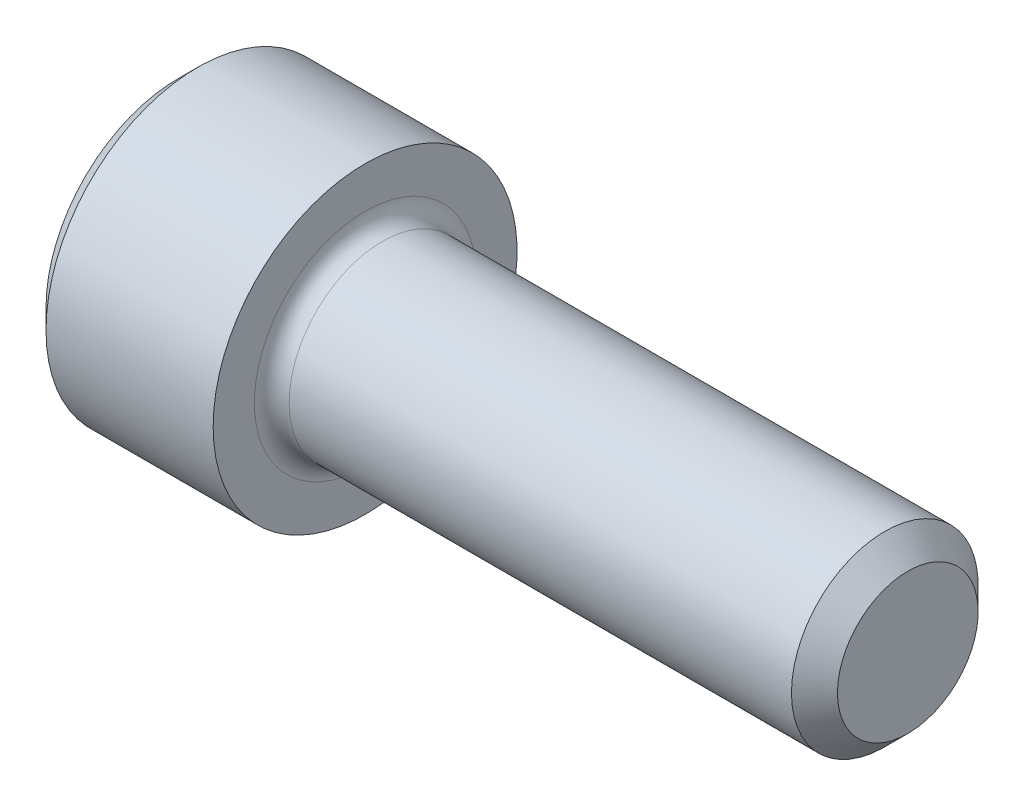
SolidWorks part; units mm, degrees
revolve "Base-Revolve" add sketch "BodySke"
sketch "BodySke" plane through (0, 0, 0) normal (0, 0, 1) x (1, 0, 0)
  line L0 (0, 0) -> (0, 1.5494)
  line L1 (0.2286, 1.778) -> (2.1844, 1.778)
  line L2 (2.1844, 1.778) -> (2.1844, 1.0922)
  line L3 (2.1844, 1.0922) -> (8.2652, 1.0922)
  line L4 (8.5344, 0.823) -> (8.5344, 0)
  line L5 (8.5344, 0) -> (0, 0)
  line L6 (-31.75, 0) -> (127, 0) construction
  line L7 (0, 1.5494) -> (0.2286, 1.778)
  line L8 (8.5344, 0.823) -> (8.2652, 1.0922)
  line L9 (0, -1.5494) -> (0.2286, -1.778) construction
  line L10 (8.5344, -0.823) -> (8.2652, -1.0922) construction
  line L11 (2.6391, 9.525) -> (2.6391, 3.175) construction
  line L12 (2.1844, 9.525) -> (2.1844, 3.175) construction
  line L13 (-29.5656, 9.525) -> (-29.5656, 3.175) construction
  dimension "Diameter" = 2.1844
  dimension "Head_ht" = 2.1844
  dimension "Length" = 6.35
  dimension "Body_ch_ang" = 45
  dimension "Head_dia" = 3.556
  dimension "Head_ch_ang" = 45
  dimension "Head_side_ht" = 1.9558
  dimension "Minor_dia" = 1.6459
  dimension "Advance" = 0.4547
  dimension "Thread_nom" = 6.35
  dimension "Thread_length" = 38.1
cosmetic thread "ThreadCosmetic" [suppressed]
fillet "Fillet1" radius 0.2032 1 edges at (2.1844, 0, 1.0922)
ref_plane "Plane1" through (0, 0, 0) normal (0, 0, 1) x (1, 0, 0)
ref_plane "Plane2" through (0, 0, 0) normal (0, 1, 0) x (1, 0, 0)
ref_plane "Plane3" through (0, 0, 0) normal (1, 0, 0) x (0, 0, -1)
sketch "Sketch2" plane through (0, 0, 0) normal (0, 0, 1) x (1, 0, 0)
  line L0 (0, 0.9906) -> (0.9652, 0.9906)
  line L1 (0.9652, 0.9906) -> (1.5371, 0)
  line L2 (-31.75, 0) -> (127, 0) construction
  line L3 (1.5371, 0) -> (0, 0)
  line L4 (0, 0) -> (0, 0.9906)
  line L5 (0, 1.5494) -> (0, -1.5494) construction
  line L6 (0, 0) -> (47.625, 0) construction
  line L7 (2.1844, -1.778) -> (2.1844, 1.778) construction
  dimension "D1" = 0.9906
  dimension "D2" = 60
revolve "Hex-PreBroach" cut sketch "Sketch2" angle 360 about L6
sketch "Sketch3" plane through (0, 0, 0) normal (-1, 0, 0) x (0, 0.5, 0.866)
  line L0 (0.5719, 0.9906) -> (-0.5719, 0.9906)
  line L1 (-0.5719, 0.9906) -> (-1.1438, 0)
  line L2 (0.5719, 0.9906) -> (1.1438, 0)
  line L3 (0.5719, -0.9906) -> (1.1438, 0)
  line L4 (0.5719, -0.9906) -> (-0.5719, -0.9906)
  line L5 (-0.5719, -0.9906) -> (-1.1438, 0)
  dimension "D1" = 0.9906
  dimension "D2" = 0.9906
  dimension "Hex_size" = 1.9812
extrude "Hex" cut sketch "Sketch3" against normal blind 0.9652
sketch "Sketch4" plane through (0, 0, 0) normal (-1, 0, 0) x (0, 0, 1)
  line L0 (0, 0) -> (1.2446, 0)
  line L1 (0, 0) -> (6.1484, 3.5498) construction
  line L2 (0, 0) -> (0.6223, 1.0779)
  line L3 (1.0085, 0.2596) -> (1.19, 0.3644)
  line L4 (0.7291, 0.7436) -> (0.9106, 0.8484)
  arc A0 (1.0085, 0.2596) -> (0.7291, 0.7436) centre (0, 0) ccw
  arc A1 (1.2446, 0) -> (1.19, 0.3644) centre (0, 0) ccw
  arc A2 (0.6223, 1.0779) -> (0.9106, 0.8484) centre (0, 0) cw
  dimension "D1" = 30
  dimension "D2" = 60
  dimension "Spline_p_dim" = 0.5588
  dimension "D3" = 0.2794
extrude "Spline" [suppressed] cut sketch "Sketch4" against normal blind 0.9652
pattern_circular "CirPattern1" [suppressed] count 6 every 60
sketch "Sketch5" plane through (0, 0, 0) normal (0, 0, 1) x (1, 0, 0)
  line L0 (-31.75, 0) -> (127, 0) construction
  line L2 (0, 1.5494) -> (0, -1.5494) construction
  circle A0 centre (0.254, 0) radius 0.0127
  dimension "Drilled_hole_dia" = 0.0254
  dimension "Drilled_hole_loc" = 0.254
extrude "Hole" [suppressed] cut sketch "Sketch5" against normal through all and the other way through all
pattern_circular "Drilled-4" [suppressed] count 2 every 60
pattern_circular "Drilled-6" [suppressed] count 3 every 60
sketch "ThdSchSke" plane through (0, 0, 0) normal (0, 0, 1) x (1, 0, 0)
  line L0 (2.6391, -0.823) -> (2.4505, -1.0922)
  line L1 (2.6391, -0.823) -> (2.8276, -1.0922)
  line L2 (2.8276, -1.0922) -> (2.8276, -1.3653)
  line L3 (-3.175, 0) -> (5.1513, 0) construction
  line L5 (2.8276, -1.3653) -> (2.4505, -1.3653)
  line L6 (2.4505, -1.3653) -> (2.4505, -1.0922)
  line L7 (0, 1.5494) -> (0, -1.5494) construction
  dimension "Thread_minor" = 1.6459
  dimension "Diameter" = 2.1844
  dimension "Start" = 2.6391
revolve "ThreadSchematic" [suppressed] cut sketch "ThdSchSke" angle 360 about L3
pattern_linear "ThdSchPat" [suppressed]
equation "\"D2@Sketch3\" = \"Hex_size@Sketch3\" / 2"
equation "\"D1@Sketch3\" = \"Hex_size@Sketch3\" / 2"
equation "\"D1@Sketch2\" = \"Hex_size@Sketch3\" / 2"
equation "\"D3@Sketch4\" = \"Spline_p_dim@Sketch4\" / 2"
equation "\"Thread_minor@ThreadCosmetic\"  =  \"Minor_dia@BodySke\""
equation "\"D2@CirPattern1\" = 360 / \"Num_teeth@CirPattern1\""
equation "\"Wall_thickness@Sketch2\" = \"Head_ht@BodySke\" - \"Key_eng@Hex\""
equation "\"Thread_length@ThreadCosmetic\" = ((sgn( (\"Length@BodySke\" - \"Advance@BodySke\" ) - \"Thread_nom@BodySke\" )-1)*( (\"Length@BodySke\" - \"Advance@BodySke\" ) - \"Thread_nom@BodySke\" ))/-2+ \"Thread_nom@BodySke\""
equation "\"Thread_minor@ThdSchSke\" = \"Minor_dia@BodySke\""
equation "\"Diameter@ThdSchSke\" = \"Diameter@BodySke\""
equation "\"Overcut@ThdSchSke\" = \"Diameter@BodySke\" * 1.25"
equation "\"Start@ThdSchSke\" = \"Head_ht@BodySke\" + \"Length@BodySke\" - \"Thread_length@ThreadCosmetic\"  '---Non-countersunk---"
equation "\"Num_threads@ThdSchPat\" = int( \"Thread_length@ThreadCosmetic\" / \"Advance@BodySke\" + 0.999 )  + 1"
equation "\"Advance@ThdSchPat\" = \"Thread_length@ThreadCosmetic\" /  (\"Num_threads@ThdSchPat\" - 1) 'relax it"
equation "\"Num_threads@ThdSchPat\" = \"Num_threads@ThdSchPat\" - sgn( \"Num_threads@ThdSchPat\" - 1) '---chamfered tips only---"
